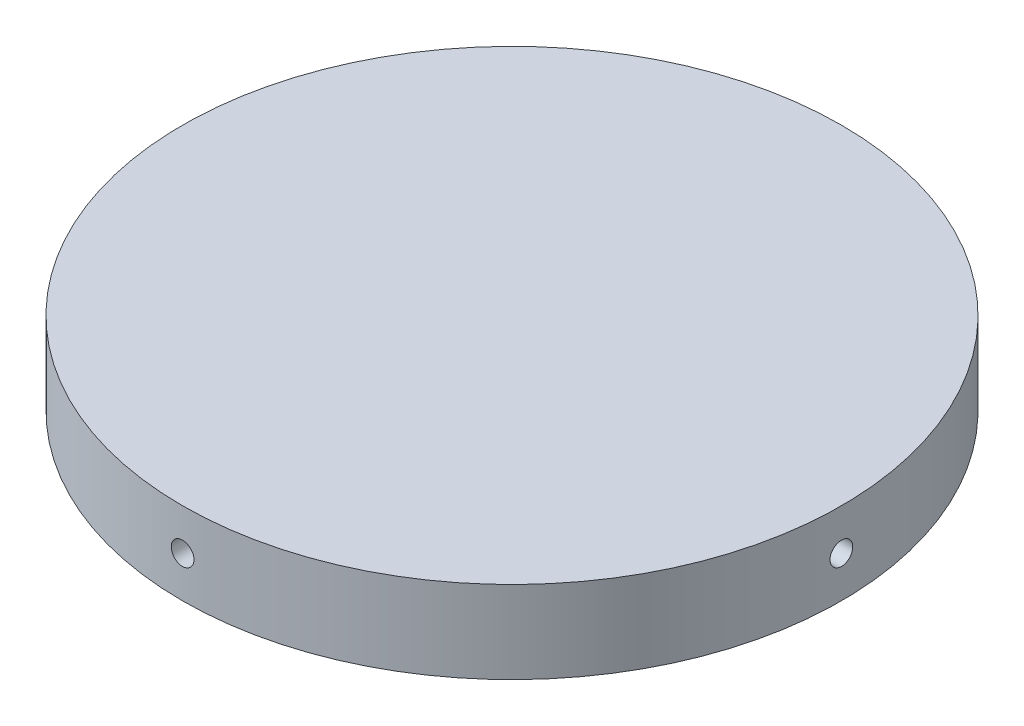
SolidWorks part; units mm, degrees
material "6061 Alloy"
ref_plane "Front Plane" through (0, 0, 0) normal (0, 0, 1) x (1, 0, 0)
ref_plane "Top Plane" through (0, 0, 0) normal (0, 1, 0) x (1, 0, 0)
ref_plane "Right Plane" through (0, 0, 0) normal (1, 0, 0) x (0, 0, -1)
sketch "Sketch1" plane through (0, 0, 0) normal (0, 1, 0) x (1, 0, 0)
  circle A0 centre (0, 0) radius 50.8
  dimension "D1" = 101.6
extrude "Boss-Extrude1" add sketch "Sketch1" along normal blind 12.7
ref_plane "Plane1" through (0, 0, 50.8) normal (0, 0, 1) x (1, 0, 0)
sketch "Sketch2" plane through (0, 0, 50.8) normal (0, 0, 1) x (1, 0, 0)
  line L0 (0, 0) -> (0, 12.7) construction
  line L1 (50.8, 12.7) -> (-50.8, 12.7) construction
  circle A0 centre (0, 6.35) radius 1.7526
  dimension "D1" = 3.5052
extrude "Cut-Extrude1" cut sketch "Sketch2" against normal blind 19.05
pattern_circular "CirPattern1" count 4 over 360 about axis through (0, 0, 0) along (0, 1, 0) of "Cut-Extrude1"
